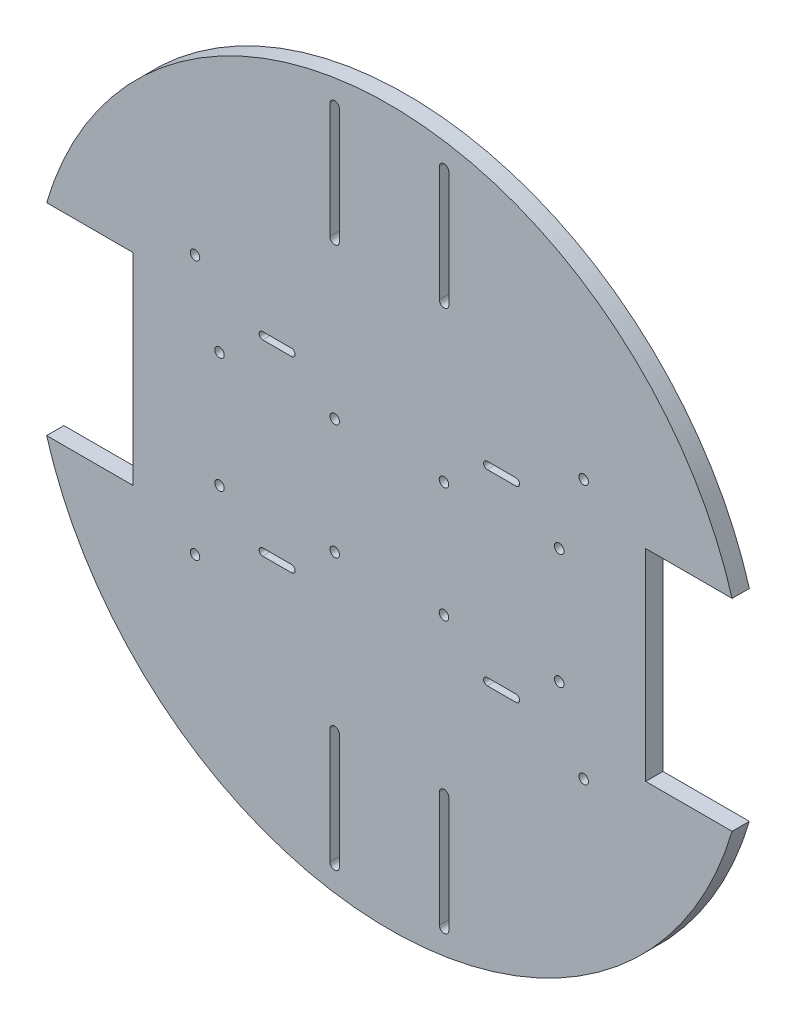
SolidWorks part; units mm, degrees
ref_plane "Plan de face" through (0, 0, 0) normal (0, 0, 1) x (1, 0, 0)
ref_plane "Plan de dessus" through (0, 0, 0) normal (0, 1, 0) x (1, 0, 0)
ref_plane "Plan de droite" through (0, 0, 0) normal (1, 0, 0) x (0, 0, -1)
sketch "Esquisse1" plane through (0, 0, 0) normal (0, 0, 1) x (1, 0, 0)
  circle A0 centre (0, 0) radius 124
  dimension "D1" = 248
extrude "Boss.-Extru.1" add sketch "Esquisse1" along normal blind 6
sketch "Esquisse2" plane through (0, 0, 6) normal (0, 0, 1) x (1, 0, 0)
  line L0 (-118.958, 35) -> (-88.958, 35)
  line L1 (-88.958, 35) -> (-88.958, -35)
  line L2 (-88.958, -35) -> (-118.958, -35)
  line L3 (118.958, 35) -> (88.958, 35)
  line L4 (88.958, 35) -> (88.958, -35)
  line L5 (88.958, -35) -> (118.958, -35)
  line L6 (-56.144, 0) -> (48.8847, 0) construction
  circle A0 centre (0, 0) radius 124 construction
  arc A1 (-118.958, 35) -> (-118.958, -35) centre (0, 0) ccw
  arc A2 (118.958, 35) -> (118.958, -35) centre (0, 0) cw
  dimension "D3" = 124
  dimension "D1" = 70
  dimension "D2" = 30
extrude "Enlèv. mat.-Extru.1" cut sketch "Esquisse2" against normal through all
sketch "Esquisse3" plane through (0, 0, 6) normal (0, 0, 1) x (1, 0, 0)
  line L0 (-88.958, -35) -> (-88.958, 35) construction
  line L1 (-61.3215, 0) -> (44.3225, 0) construction
  circle A0 centre (-58.958, 20) radius 1.65
  circle A1 centre (-18.958, 20) radius 1.65
  circle A2 centre (-18.958, -20) radius 1.65
  circle A3 centre (-58.958, -20) radius 1.65
  dimension "D1" = 3.3
  dimension "D2" = 40
  dimension "D3" = 40
  dimension "D4" = 30
  dimension "D5" = 70
extrude "Enlèv. mat.-Extru.3" cut sketch "Esquisse3" against normal through all
sketch "Esquisse5" plane through (0, 0, 6) normal (0, 0, 1) x (1, 0, 0)
  line L0 (-88.958, -35) -> (-88.958, 35) construction
  line L1 (0, 0) -> (-81.7789, 0) construction
  circle A0 centre (-67.458, 45) radius 1.65
  circle A1 centre (-67.458, -45) radius 1.65
  dimension "D1" = 3.3
  dimension "D3" = 21.5
  dimension "D2" = 90
extrude "Enlèv. mat.-Extru.4" cut sketch "Esquisse5" against normal through all
sketch "Esquisse6" plane through (0, 0, 6) normal (0, 0, 1) x (1, 0, 0)
  line L0 (-43.958, 32.5) -> (-33.958, 32.5) construction
  line L1 (-43.958, 33.75) -> (-33.958, 33.75)
  line L2 (-43.958, 31.25) -> (-33.958, 31.25)
  line L3 (-43.958, -32.5) -> (-33.958, -32.5) construction
  line L4 (-43.958, -31.25) -> (-33.958, -31.25)
  line L5 (-43.958, -33.75) -> (-33.958, -33.75)
  line L6 (-88.958, -35) -> (-88.958, 35) construction
  line L7 (0, 0) -> (-75.1686, 0) construction
  arc A0 (-43.958, 33.75) -> (-43.958, 31.25) centre (-43.958, 32.5) ccw
  arc A1 (-33.958, 31.25) -> (-33.958, 33.75) centre (-33.958, 32.5) ccw
  arc A2 (-43.958, -31.25) -> (-43.958, -33.75) centre (-43.958, -32.5) ccw
  arc A3 (-33.958, -33.75) -> (-33.958, -31.25) centre (-33.958, -32.5) ccw
  point P2 (-38.958, 32.5)
  point P7 (-38.958, -32.5)
  dimension "D1" = 10
  dimension "D2" = 2.5
  dimension "D3" = 65
  dimension "D4" = 50
extrude "Enlèv. mat.-Extru.5" cut sketch "Esquisse6" against normal through all
sketch "Esquisse7" plane through (0, 0, 6) normal (0, 0, 1) x (1, 0, 0)
  line L0 (-19, 114) -> (-19, 74) construction
  line L1 (-17.35, 114) -> (-17.35, 74)
  line L2 (-20.65, 114) -> (-20.65, 74)
  line L3 (-19, -74) -> (-19, -114) construction
  line L4 (-17.35, -74) -> (-17.35, -114)
  line L5 (-20.65, -74) -> (-20.65, -114)
  line L6 (0, 49.7279) -> (0, -17.0114) construction
  line L7 (-34.6131, 0) -> (53.4933, 0) construction
  line L8 (-83.6878, 124) -> (71.1304, 124) construction
  arc A0 (-17.35, 114) -> (-20.65, 114) centre (-19, 114) ccw
  arc A1 (-20.65, 74) -> (-17.35, 74) centre (-19, 74) ccw
  arc A2 (-17.35, -74) -> (-20.65, -74) centre (-19, -74) ccw
  arc A3 (-20.65, -114) -> (-17.35, -114) centre (-19, -114) ccw
  arc A5 (118.958, 35) -> (-118.958, 35) centre (0, 0) ccw construction
  point P2 (-19, 94)
  point P7 (-19, -94)
  dimension "D4" = 10
  dimension "D1" = 3.3
  dimension "D2" = 19
  dimension "D3" = 40
extrude "Enlèv. mat.-Extru.6" cut sketch "Esquisse7" against normal through all
mirror "Symétrie2" about plane through (0, 0, 0) normal (1, 0, 0) of "Enlèv. mat.-Extru.3", "Enlèv. mat.-Extru.4", "Enlèv. mat.-Extru.5", "Enlèv. mat.-Extru.6"
